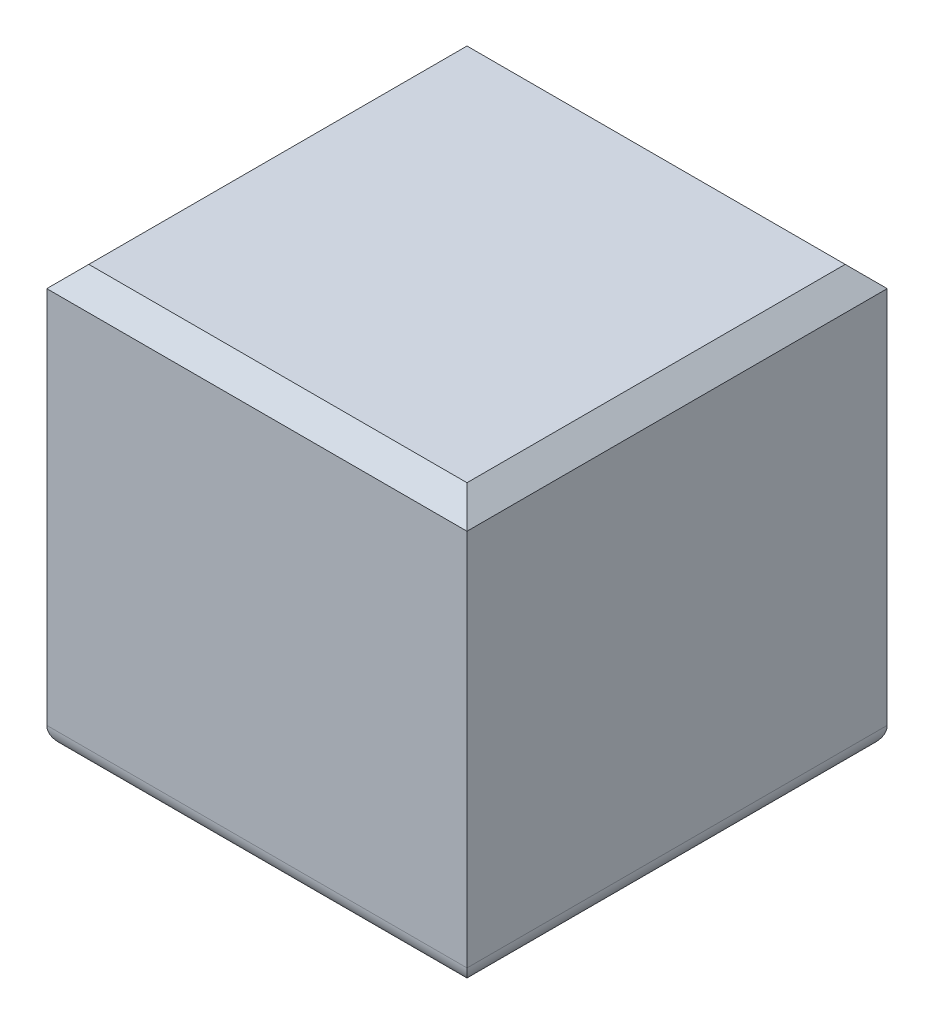
SolidWorks part; units mm, degrees
ref_plane "Front Plane" through (0, 0, 0) normal (0, 0, 1) x (1, 0, 0)
ref_plane "Top Plane" through (0, 0, 0) normal (0, 1, 0) x (1, 0, 0)
ref_plane "Right Plane" through (0, 0, 0) normal (1, 0, 0) x (0, 0, -1)
other "Configuration Table"
sketch "Sketch1" plane through (0, 0, 0) normal (0, 1, 0) x (1, 0, 0)
  line L1 (50, -50) -> (-50, -50)
  line L2 (50, -50) -> (50, 50)
  line L3 (50, 50) -> (-50, 50)
  line L4 (-50, -50) -> (-50, 50)
  line L5 (50, -50) -> (-50, 50) construction
  line L6 (50, 50) -> (-50, -50) construction
  point P0 (0, 0)
  dimension "D1" = 100
extrude "Boss-Extrude1" add sketch "Sketch1" along normal blind 100
fillet "Fillet1" radius 5 4 edges at (0, 0, -50) (50, 0, 0) (0, 0, 50) (-50, 0, 0)
chamfer "Chamfer2" distance 5 angle 45 4 edges at (50, 100, 0) (0, 100, 50) (-50, 100, 0) (0, 100, -50)
